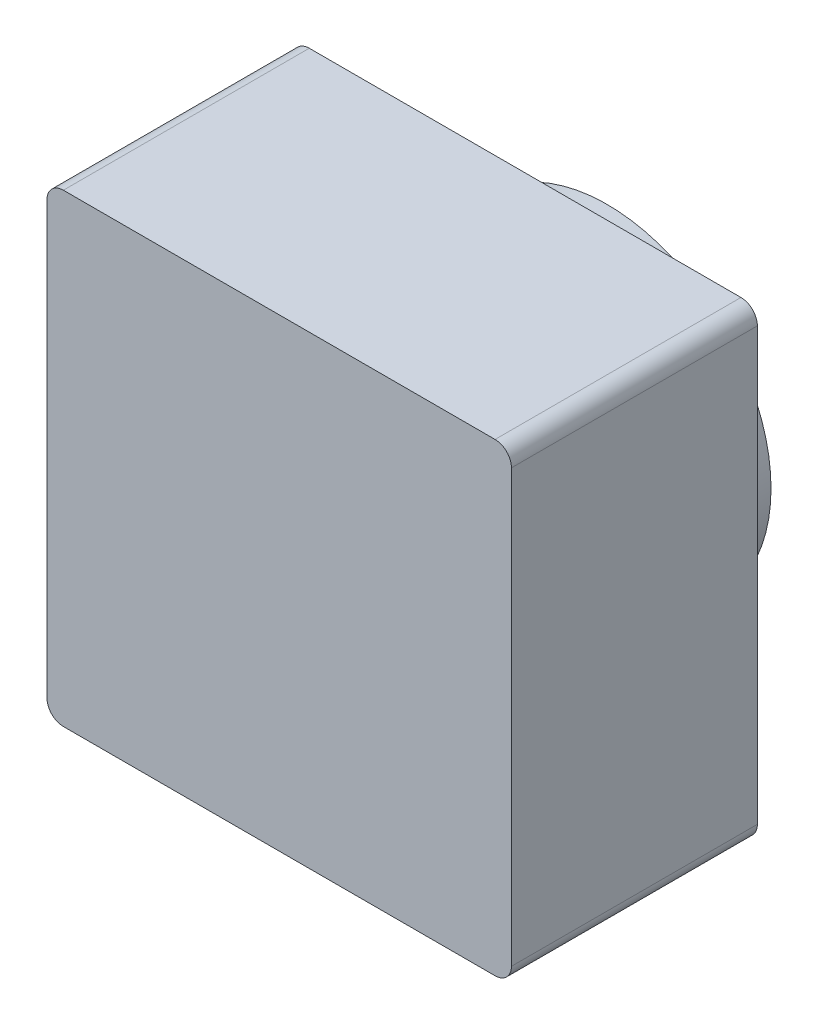
SolidWorks part; units mm, degrees
ref_plane "Front Plane" through (0, 0, 0) normal (0, 0, 1) x (1, 0, 0)
ref_plane "Top Plane" through (0, 0, 0) normal (0, 1, 0) x (1, 0, 0)
ref_plane "Right Plane" through (0, 0, 0) normal (1, 0, 0) x (0, 0, -1)
ref_plane "PZ_m10_20" through (0, 0, -10.2) normal (0, 0, 1) x (1, 0, 0)
sketch "Body_Sk1" plane through (0, 0, -10.2) normal (0, 0, 1) x (1, 0, 0)
  line L0 (-20.31, 5.69) -> (-12.41, 5.69)
  line L1 (-12.11, 5.99) -> (-12.11, 13.89)
  line L2 (-12.41, 14.19) -> (-20.31, 14.19)
  line L3 (-20.61, 13.89) -> (-20.61, 5.99)
  arc A0 (-20.61, 5.99) -> (-20.31, 5.69) centre (-20.31, 5.99) ccw
  arc A1 (-12.41, 5.69) -> (-12.11, 5.99) centre (-12.41, 5.99) ccw
  arc A2 (-12.11, 13.89) -> (-12.41, 14.19) centre (-12.41, 13.89) ccw
  arc A3 (-20.31, 14.19) -> (-20.61, 13.89) centre (-20.31, 13.89) ccw
extrude "Body" add sketch "Body_Sk1" against normal blind 4.5
ref_plane "PZ_m14_70" through (0, 0, -14.7) normal (0, 0, 1) x (1, 0, 0)
sketch "Lens_Sk2" plane through (0, 0, -14.7) normal (0, 0, 1) x (1, 0, 0)
  circle A0 centre (-16.36, 9.94) radius 3
extrude "Lens" add sketch "Lens_Sk2" against normal blind 1.5
